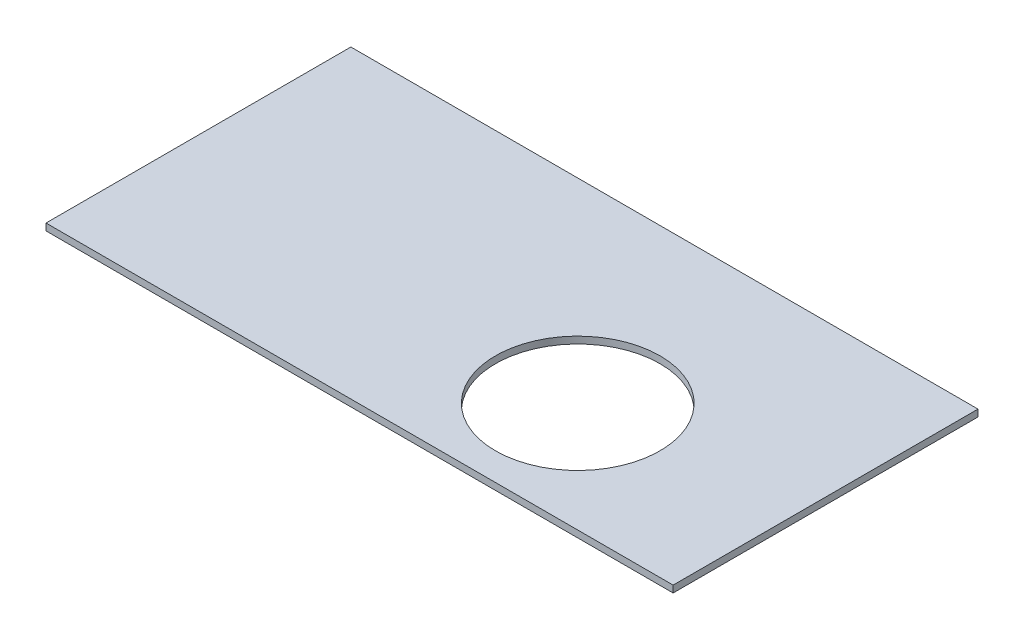
SolidWorks part; units mm, degrees
material "ABS"
ref_plane "Front Plane" through (0, 0, 0) normal (0, 0, 1) x (1, 0, 0)
ref_plane "Top Plane" through (0, 0, 0) normal (0, 1, 0) x (1, 0, 0)
ref_plane "Right Plane" through (0, 0, 0) normal (1, 0, 0) x (0, 0, -1)
sketch "Sketch1" plane through (0, 0, 0) normal (0, 1, 0) x (1, 0, 0)
  line L1 (228.6, -111.125) -> (-228.6, -111.125)
  line L2 (228.6, -111.125) -> (228.6, 111.125)
  line L3 (228.6, 111.125) -> (-228.6, 111.125)
  line L4 (-228.6, -111.125) -> (-228.6, 111.125)
  line L5 (228.6, -111.125) -> (-228.6, 111.125) construction
  line L6 (228.6, 111.125) -> (-228.6, -111.125) construction
  point P0 (0, 0)
  dimension "D1" = 457.2
  dimension "D2" = 222.25
extrude "Boss-Extrude1" add sketch "Sketch1" along normal blind 5
sketch "Sketch2" plane through (0, 5, 0) normal (0, 1, 0) x (1, 0, 0)
  line L0 (-228.6, -111.125) -> (228.6, -111.125) construction
  line L1 (228.6, -111.125) -> (228.6, 111.125) construction
  circle A0 centre (79.05, -31.125) radius 60
  dimension "D1" = 120
  dimension "D2" = 80
  dimension "D3" = 149.55
extrude "Cut-Extrude1" cut sketch "Sketch2" against normal through all
